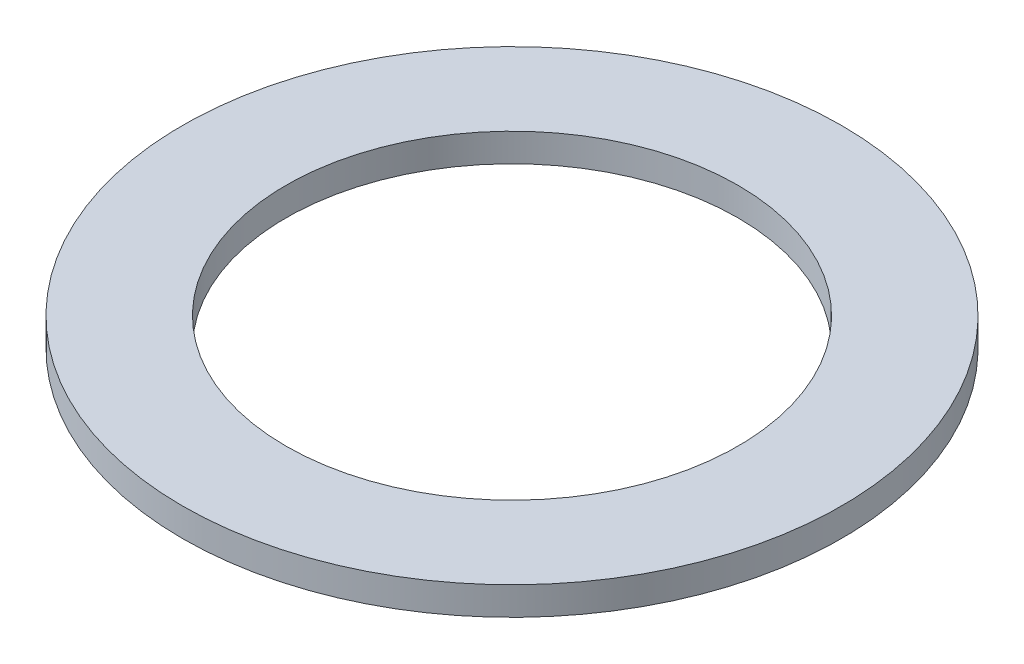
SolidWorks part; units mm, degrees
material "Kauczuk naturalny"
ref_plane "Płaszczyzna przednia" through (0, 0, 0) normal (0, 0, 1) x (1, 0, 0)
ref_plane "Płaszczyzna górna" through (0, 0, 0) normal (0, 1, 0) x (1, 0, 0)
ref_plane "Płaszczyzna prawa" through (0, 0, 0) normal (1, 0, 0) x (0, 0, -1)
sketch "Szkic1" plane through (0, 0, 0) normal (0, 1, 0) x (1, 0, 0)
  circle A0 centre (0, 0) radius 12
  circle A1 centre (0, 0) radius 17.5
  dimension "D1" = 35
  dimension "D2" = 24
extrude "Dodanie-wyciągnięcie1" add sketch "Szkic1" along normal blind 1.5
